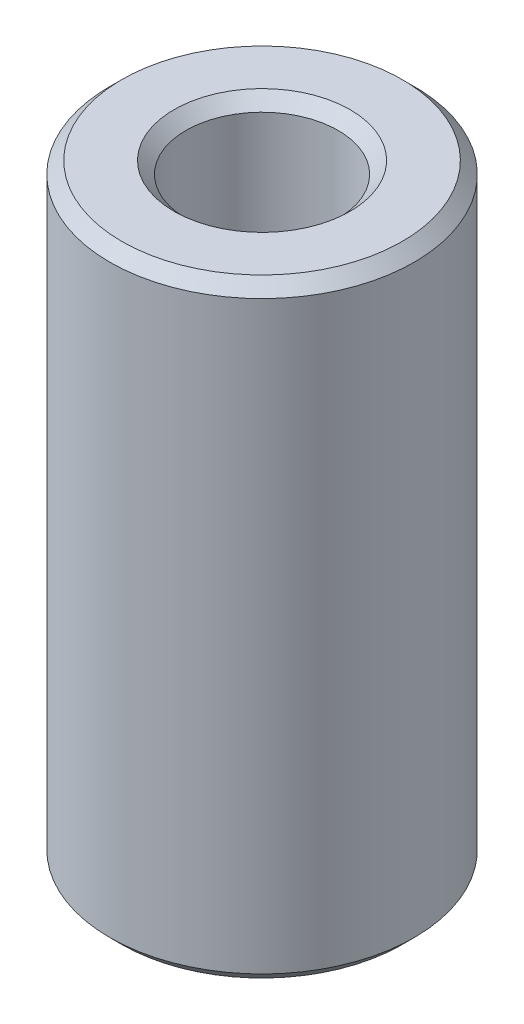
SolidWorks part; units mm, degrees
material "6061-T6 (SS)"
ref_plane "Front Plane" through (0, 0, 0) normal (0, 0, 1) x (1, 0, 0)
ref_plane "Top Plane" through (0, 0, 0) normal (0, 1, 0) x (1, 0, 0)
ref_plane "Right Plane" through (0, 0, 0) normal (1, 0, 0) x (0, 0, -1)
sketch "Sketch1" plane through (0, 0, 0) normal (0, 1, 0) x (1, 0, 0)
  circle A0 centre (0, 0) radius 6.35
  circle A1 centre (0, 0) radius 3.175
  dimension "D1" = 12.7
  dimension "D2" = 3.175
extrude "Boss-Extrude1" add sketch "Sketch1" along normal blind 25.4
chamfer "Chamfer1" distance 0.5 angle 45 4 edges at (0, 0, 6.35) (0, 0, 3.175) (0, 25.4, 6.35) (0, 25.4, 3.175)
